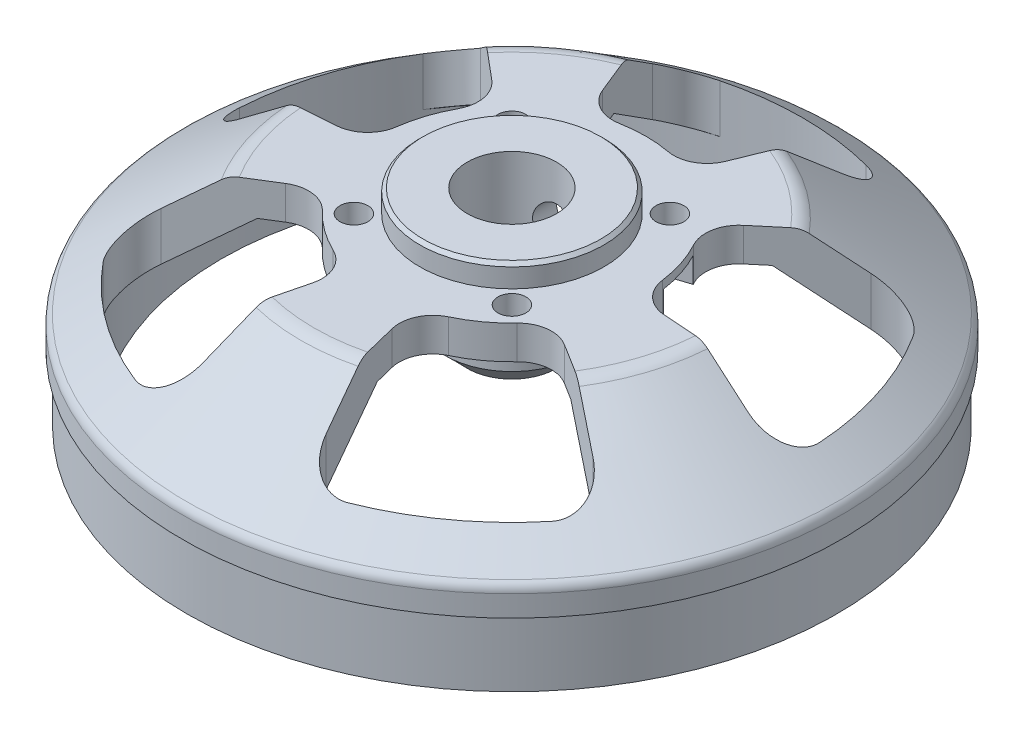
SolidWorks part; units mm, degrees
ref_plane "Front Plane" through (0, 0, 0) normal (0, 0, 1) x (1, 0, 0)
ref_plane "Top Plane" through (0, 0, 0) normal (0, 1, 0) x (1, 0, 0)
ref_plane "Right Plane" through (0, 0, 0) normal (1, 0, 0) x (0, 0, -1)
sketch "Sketch1" plane through (0, 0, 0) normal (0, 1, 0) x (1, 0, 0)
  circle A1 centre (0, 0) radius 29.075
  circle A2 centre (0, 0) radius 26
  dimension "D1" = 58.15
extrude "Boss-Extrude1" add sketch "Sketch1" against normal blind 6
sketch "Sketch2" plane through (0, 0, 0) normal (0, 1, 0) x (1, 0, 0)
  circle A0 centre (0, 0) radius 29.5
sketch "Sketch4" plane through (0, 0, 0) normal (1, 0, 0) x (0, 0, -1)
  line L0 (0, 0) -> (0, 21) construction
  line L1 (29.5, 0) -> (-29.5, 0) construction
  line L2 (29.5, 0) -> (26, 0)
  line L3 (-29.5, 0) -> (-29.5, 1.8909)
  line L4 (-29.0883, 2.6995) -> (-18.8915, 10.1173)
  line L5 (-17.715, 10.5) -> (-8.25, 10.5)
  line L6 (-4, 10.5) -> (-4, 7.5)
  line L7 (-4, 7.5) -> (-16.5398, 7.5)
  line L8 (-16.5398, 7.5) -> (-26, 0.618)
  line L9 (-26, 0.618) -> (-26, 0)
  line L10 (-7.95, 12.5) -> (-8.25, 12.2)
  line L11 (-4, 10.5) -> (-4, 12.5)
  line L12 (-26, 0) -> (-29.5, 0)
  line L13 (-4, 12.5) -> (-7.95, 12.5)
  line L14 (-8.25, 12.2) -> (-8.25, 10.5)
  arc A0 (-18.8915, 10.1173) -> (-17.715, 10.5) centre (-17.715, 8.5) cw
  arc A1 (-29.5, 1.8909) -> (-29.0883, 2.6995) centre (-28.5, 1.8909) cw
  point P15 (-8.25, 12.5)
  point P22 (-29.5, 2.4)
  dimension "D8" = 2
  dimension "D9" = 1
  dimension "D1" = 3
  dimension "D2" = 3.5
  dimension "D3" = 10.5
  dimension "D4" = 2.4
  dimension "D5" = 4
  dimension "D6" = 8.25
  dimension "D7" = 2
revolve "Revolve3" add sketch "Sketch4" angle 360 about L0
sketch "Sketch5" plane through (0, 10.5, 0) normal (0, 1, 0) x (1, 0, 0)
  line L0 (0, 0) -> (0, 30.8593) construction
  line L1 (-5.5114, 13.6244) -> (-8.5513, 21.1394)
  line L2 (5.5114, 13.6244) -> (8.5513, 21.1394)
  arc A0 (2.1842, 11.7995) -> (-2.1842, 11.7995) centre (0, 0) ccw
  arc A1 (6.5229, 25.1685) -> (-6.5229, 25.1685) centre (0, 0) ccw
  circle A2 centre (0, 0) radius 29.5 construction
  arc A3 (-5.5114, 13.6244) -> (-2.1842, 11.7995) centre (-2.7303, 14.7494) ccw
  arc A4 (-6.5229, 25.1685) -> (-8.5513, 21.1394) centre (-5.7702, 22.2644) ccw
  arc A5 (6.5229, 25.1685) -> (8.5513, 21.1394) centre (5.7702, 22.2644) cw
  arc A6 (5.5114, 13.6244) -> (2.1842, 11.7995) centre (2.7303, 14.7494) cw
  point P13 (-9.75, 24.1026)
  dimension "D1" = 3.5
  dimension "D2" = 24
  dimension "D3" = 9.75
  dimension "D4" = 3
  dimension "D5" = 3
extrude "Cut-Extrude1" cut sketch "Sketch5" against normal through all
sketch "Sketch6" plane through (0, 0, 0) normal (0, 0, 1) x (1, 0, 0)
  line L0 (0, 0) -> (0, 15.3619) construction
pattern_circular "CirPattern1" count 5 over 360 about axis through (0, 0, 0) along (0, 1, 0) of "Cut-Extrude1"
sketch "Sketch7" plane through (0, 10.5, 0) normal (0, 1, 0) x (1, 0, 0)
  circle A0 centre (0, 0) radius 10
  circle A1 centre (0, 10) radius 1.25
  arc A2 (-10.5471, 5.7236) -> (-11.897, 1.5689) centre (0, 0) ccw construction
  circle A3 centre (7.0711, 7.0711) radius 1.25
  circle A4 centre (10, 0) radius 1.25
  circle A5 centre (7.0711, -7.0711) radius 1.25
  circle A6 centre (0, -10) radius 1.25
  circle A7 centre (-7.0711, -7.0711) radius 1.25
  circle A8 centre (-10, 0) radius 1.25
  circle A9 centre (-7.0711, 7.0711) radius 1.25
  point P5 (-11.4127, 3.7082)
  point P26 (0, 0)
  dimension "D1" = 8
extrude "Cut-Extrude2" cut sketch "Sketch7" against normal through all contours A9 | A7 | A5 | A3
sketch "Sketch8" plane through (0, 7.5, 0) normal (0, -1, 0) x (-1, 0, 0)
  circle A0 centre (0, 0) radius 6
extrude "Boss-Extrude3" add sketch "Sketch8" along normal blind 7
chamfer "Chamfer2" distance 2 angle 45 1 edges at (0, 0.5, -6)
sketch "Sketch9" plane through (0, 0.5, 0) normal (0, -1, 0) x (-1, 0, 0)
  circle A0 centre (0, 0) radius 4
  dimension "D1" = 8
extrude "Cut-Extrude3" cut sketch "Sketch9" against normal through all
ref_plane "Plane2" through (0, 0, -11.7995) normal (0, 0, -1) x (-1, 0, 0)
sketch "Sketch10" plane through (0, 7.5, 0) normal (0, -1, 0) x (1, 0, 0)
  line L0 (2.075, -15.925) -> (2.075, -8.075)
  line L1 (2.075, -15.925) -> (-2.075, -15.925)
  line L2 (2.075, -8.075) -> (-2.075, -8.075)
  line L3 (-2.075, -15.925) -> (-2.075, -8.075)
  line L4 (2.075, -15.925) -> (-2.075, -8.075) construction
  line L5 (2.075, -8.075) -> (-2.075, -15.925) construction
  arc A0 (-2.1842, -11.7995) -> (2.1842, -11.7995) centre (0, 0) ccw construction
  arc A1 (2.075, -8.075) -> (-2.075, -8.075) centre (0, -8.075) ccw
  circle A2 centre (0, 0) radius 6 construction
  point P0 (0, -12)
  point P1 (0, -12)
  point P10 (0, -6)
  point P11 (0, -6)
  arc M15 (-2.1842, -11.7995) -> (2.1842, -11.7995) centre (0, 0) ccw
  dimension "D1" = 4.15
  dimension "D2" = 0
  dimension "D3" = 0
extrude "Cut-Extrude4" cut sketch "Sketch10" against normal blind 2.25 contours L3 L0 L2 M15 | L2 A1
sketch "Sketch11" plane through (0, 0, -11.7995) normal (0, 0, -1) x (-1, 0, 0)
  line L0 (0, 7.5) -> (2.075, 7.5) construction
  line L1 (0, 7.5) -> (2.075, 7.5)
  circle A0 centre (0, 7.5) radius 1.75
  dimension "D1" = 3.5
extrude "Cut-Extrude5" cut sketch "Sketch11" against normal blind 11 contours A0
pattern_circular "CirPattern2" count 2 over 72 about axis through (0, 0, 0) along (0, 1, 0) of "Cut-Extrude4", "Cut-Extrude5"
